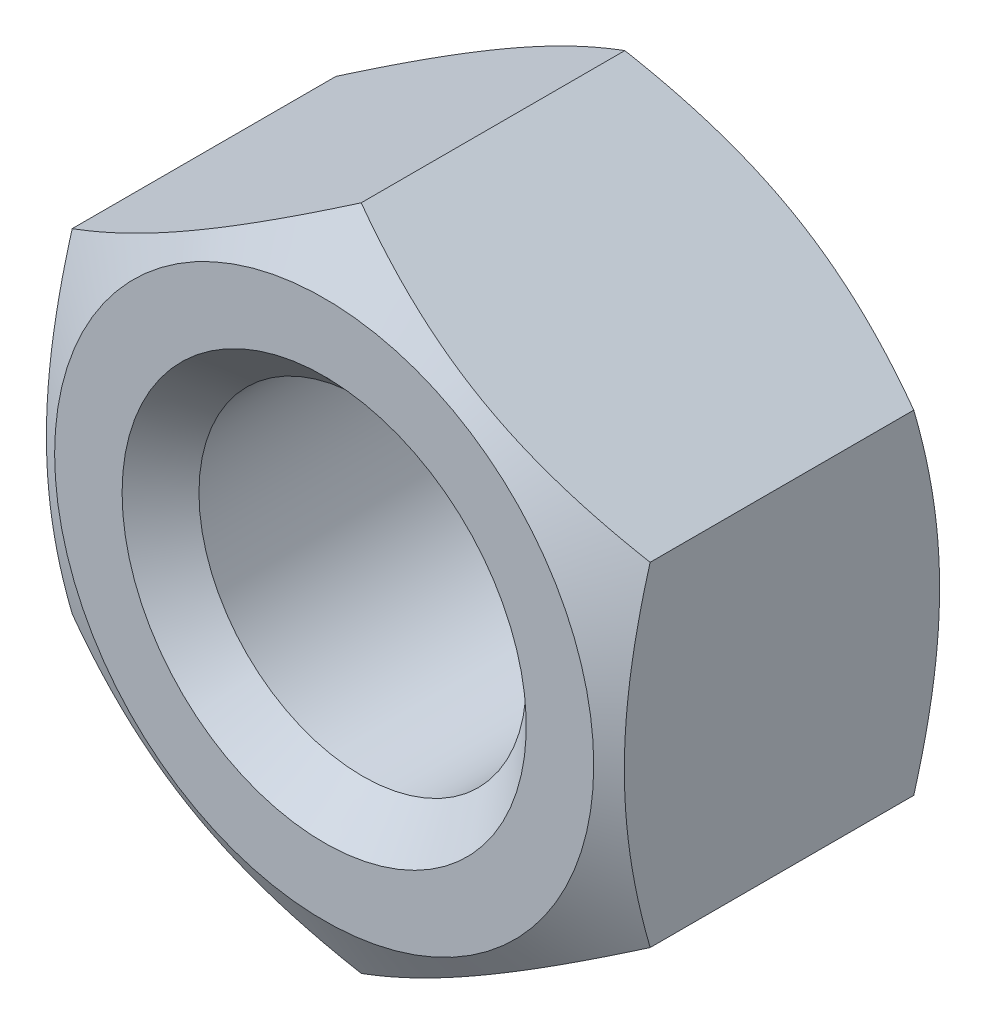
SolidWorks part; units mm, degrees
ref_plane "front" through (0, 0, 0) normal (0, 0, 1) x (1, 0, 0)
ref_plane "top" through (0, 0, 0) normal (0, 1, 0) x (1, 0, 0)
ref_plane "right" through (0, 0, 0) normal (1, 0, 0) x (0, 0, -1)
sketch "Sketch1" plane through (0, 0, 0) normal (1, 0, 0) x (0, 0, -1)
  line L0 (-1.5843, 6.7469) -> (-12.3349, 6.7469)
  line L1 (-12.3349, 6.7469) -> (-13.9192, 8.3312)
  line L2 (-13.9192, 8.3312) -> (-13.9192, 11.1125)
  line L3 (-13.9192, 11.1125) -> (-11.1696, 15.875)
  line L4 (-11.1696, 15.875) -> (-2.7496, 15.875)
  line L5 (-2.7496, 15.875) -> (0, 11.1125)
  line L6 (0, 11.1125) -> (0, 8.3312)
  line L7 (0, 8.3312) -> (-1.5843, 6.7469)
  line L8 (-6.9596, 15.875) -> (-6.9596, 26.7712) construction
  line L9 (0, 0) -> (22.4968, 0) construction
  dimension "D1" = 45
  dimension "D2" = 30
  dimension "D3" = 22.225
  dimension "D4" = 13.4937
  dimension "D5" = 16.6624
  dimension "D6" = 31.75
  dimension "D7" = 13.9192
ref_axis "Axis1" through (0, 0, -10.3808) along (0, 0, 1)
revolve "Revolve1" add sketch "Sketch1" angle 360 about axis through (0, 0, -10.3808) along (0, 0, 1)
sketch "Sketch2" plane through (0, 0, 0) normal (0, 0, 1) x (1, 0, 0)
  line L1 (0, 13.7555) -> (-11.9126, 6.8777)
  line L2 (-11.9126, 6.8777) -> (-11.9126, -6.8777)
  line L3 (-11.9126, -6.8777) -> (0, -13.7555)
  line L4 (0, -13.7555) -> (11.9126, -6.8777)
  line L5 (11.9126, -6.8777) -> (11.9126, 6.8777)
  line L6 (11.9126, 6.8777) -> (0, 13.7555)
  circle A0 centre (0, 0) radius 11.9126 construction
  dimension "D1" = 23.8252
extrude "Cut-Extrude2" cut sketch "Sketch2" along normal blind 25.4 flip side to cut
